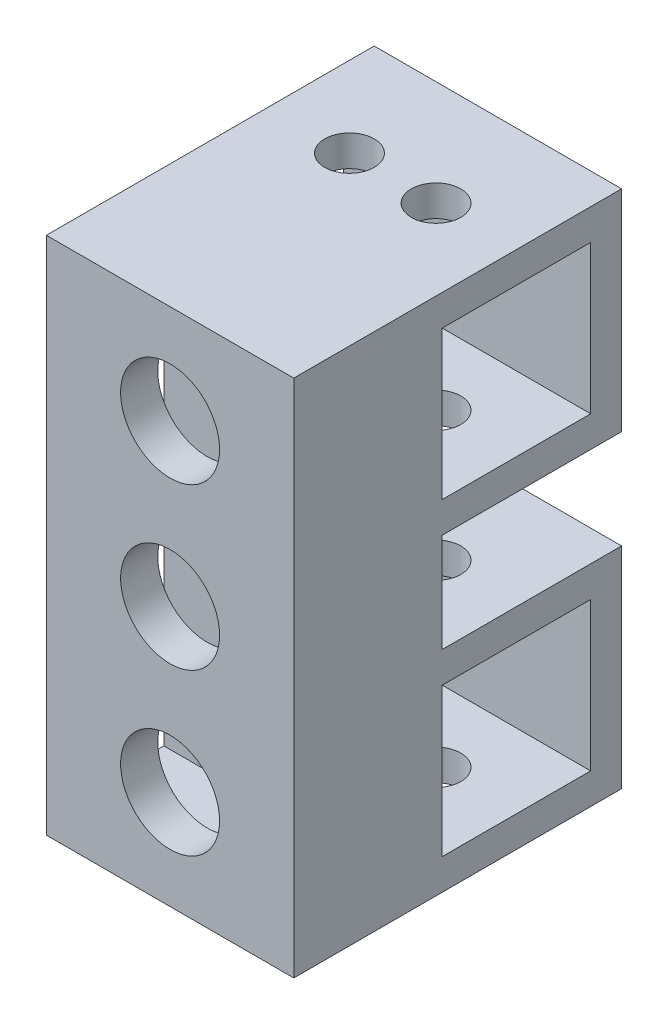
SolidWorks part; units mm, degrees
ref_plane "Plan de face" through (0, 0, 0) normal (0, 0, 1) x (1, 0, 0)
ref_plane "Plan de dessus" through (0, 0, 0) normal (0, 1, 0) x (1, 0, 0)
ref_plane "Plan de droite" through (0, 0, 0) normal (1, 0, 0) x (0, 0, -1)
sketch "Esquisse1" plane through (0, 0, 0) normal (0, 0, 1) x (1, 0, 0)
  line L0 (0, -49.5) -> (0, -41.5)
  line L1 (0, 0) -> (20, 0)
  line L2 (0, 0) -> (0, -42)
  line L3 (0, -42) -> (20, -42)
  line L4 (20, 0) -> (20, -42)
  line L6 (20, 0) -> (20, -42)
  line L7 (20, -10.5) -> (20, -18.5)
  line L11 (0, -10.5) -> (0, -18.5)
  line L15 (20, -41.5) -> (20, -49.5)
  line L19 (0, -41.5) -> (0, -49.5)
  line L22 (0, -18.5) -> (0, -10.5)
  line L23 (20, -10.5) -> (20, -18.5)
  line L24 (20, -41.5) -> (20, -49.5)
  line L25 (20, -49.5) -> (20.1497, -49.6465)
  dimension "D4" = 42
  dimension "D5" = 20
extrude "Boss.-Extru.1" add sketch "Esquisse1" along normal blind 12
sketch "Esquisse2" plane through (0, 0, 0) normal (0, 0, -1) x (-1, 0, 0)
  line L0 (0, -42) -> (-20, -42) construction
  line L1 (0, -42) -> (-20, -42)
  line L2 (0, -42) -> (0, -25)
  line L3 (0, -25) -> (-20, -25)
  line L4 (-20, -42) -> (-20, -25)
  line L5 (0, 0) -> (0, -42) construction
  line L6 (-20, 0) -> (-20, -42) construction
  line L8 (-20, 0) -> (-20, -42) construction
  point P6 (-20, -21)
  point P8 (-20, -33.5)
  dimension "D1" = 17
  dimension "D2" = 12.5
  dimension "D4" = 0
  dimension "D5" = 0
  dimension "D6" = 8.5
extrude "Boss.-Extru.3" add sketch "Esquisse2" along normal blind 14.5
sketch "Esquisse3" plane through (20, 0, 0) normal (1, 0, 0) x (0, 0, -1)
  line L0 (0, 0) -> (0, -25) construction
  line L1 (12, -39.5) -> (0, -39.5)
  line L2 (12, -39.5) -> (12, -27.5)
  line L3 (12, -27.5) -> (0, -27.5)
  line L4 (0, -39.5) -> (0, -27.5)
  line L5 (14.5, -42) -> (-12, -42) construction
  dimension "D1" = 12
  dimension "D2" = 12
  dimension "D3" = 0
  dimension "D4" = 2.5
extrude "Enlèv. mat.-Extru.3" cut sketch "Esquisse3" against normal through all
ref_plane "Plan1" through (0, -21, 0) normal (0, -1, 0) x (-1, 0, 0)
mirror "Symétrie1" about plane through (0, -21, 0) normal (0, -1, 0) of "Boss.-Extru.3", "Enlèv. mat.-Extru.3"
sketch "Esquisse4" plane through (0, -42, 0) normal (0, -1, 0) x (1, 0, 0)
  line L1 (0, -12) -> (20, -12) construction
  line L2 (20, -14.5) -> (0, -14.5) construction
  circle A0 centre (13.5, -6) radius 2
  circle A1 centre (6.5, -6) radius 2
  point P10 (10, -14.5)
  dimension "D1" = 6
  dimension "D3" = 4
  dimension "D4" = 4
  dimension "D2" = 3.5
  dimension "D5" = 7
  dimension "D6" = 8.5
extrude "Enlèv. mat.-Extru.4" cut sketch "Esquisse4" against normal blind 42
ref_plane "Plan2" through (10, 0, 0) normal (-1, 0, 0) x (0, 0, 1)
sketch "Esquisse5" plane through (0, 0, 12) normal (0, 0, 1) x (1, 0, 0)
  line L0 (0, -42) -> (20, -42) construction
  line L1 (6.2472, -40.5) -> (13.7528, -40.5)
  line L2 (13.7528, -40.5) -> (17.5056, -34)
  line L3 (17.5056, -34) -> (13.7528, -27.5)
  line L4 (13.7528, -27.5) -> (6.2472, -27.5)
  line L5 (6.2472, -27.5) -> (2.4944, -34)
  line L6 (2.4944, -34) -> (6.2472, -40.5)
  line L7 (13.7528, -14.5) -> (17.5056, -8)
  line L8 (17.5056, -8) -> (13.7528, -1.5)
  line L9 (13.7528, -1.5) -> (6.2472, -1.5)
  line L10 (6.2472, -1.5) -> (2.4944, -8)
  line L11 (2.4944, -8) -> (6.2472, -14.5)
  line L12 (6.2472, -14.5) -> (13.7528, -14.5)
  line L13 (6.2472, -14.5) -> (2.4944, -21)
  line L14 (2.4944, -21) -> (6.2472, -27.5)
  line L15 (6.2472, -27.5) -> (13.7528, -27.5)
  line L16 (13.7528, -27.5) -> (17.5056, -21)
  line L17 (17.5056, -21) -> (13.7528, -14.5)
  line L18 (13.7528, -14.5) -> (6.2472, -14.5)
  line L19 (-11, -21) -> (11, -21) construction
  line L20 (10, 14.575) -> (10, -14.575) construction
  line L21 (6.2472, -40.5) -> (0, -40.5)
  line L22 (0, 0) -> (0, -42) construction
  line L23 (0, -40.5) -> (0, -1.5)
  line L24 (0, -1.5) -> (6.2472, -1.5)
  circle A0 centre (10, -34) radius 6.5 construction
  circle A1 centre (10, -8) radius 6.5 construction
  circle A2 centre (10, -21) radius 6.5 construction
  line M9 (0, 0) -> (0, -42)
  dimension "D1" = 13
  dimension "D2" = 13
  dimension "D3" = 13
  dimension "D4" = 0
  dimension "D5" = 0
  dimension "D6" = 360
  dimension "D7" = 0
  dimension "D8" = 6.5
  dimension "D9" = 0
  dimension "D10" = 0
  dimension "D11" = 0
  dimension "D12" = 13
  dimension "D13" = 180
extrude "Enlèv. mat.-Extru.5" cut sketch "Esquisse5" against normal blind 6.5 from offset 3 contours L16 L17 L12 L13 L14 L4 | L5 L6 L1 L2 L3 L4 | L24 L21 L6 L5 L14 L13 L11 L10 M9 | L11 L12 L7 L8 L9 L10 offset against normal yes
sketch "Esquisse6" plane through (0, 0, 12) normal (0, 0, 1) x (1, 0, 0)
  circle A0 centre (10, -34) radius 4
  circle A1 centre (10, -21) radius 4
  circle A2 centre (10, -8) radius 4
  dimension "D1" = 8
  dimension "D2" = 8
  dimension "D3" = 8
extrude "Enlèv. mat.-Extru.6" cut sketch "Esquisse6" against normal blind 13.5
equation "\"é\"=1.5583"
equation "\"à\"=2.55842"
equation "\"éà\"=42"
